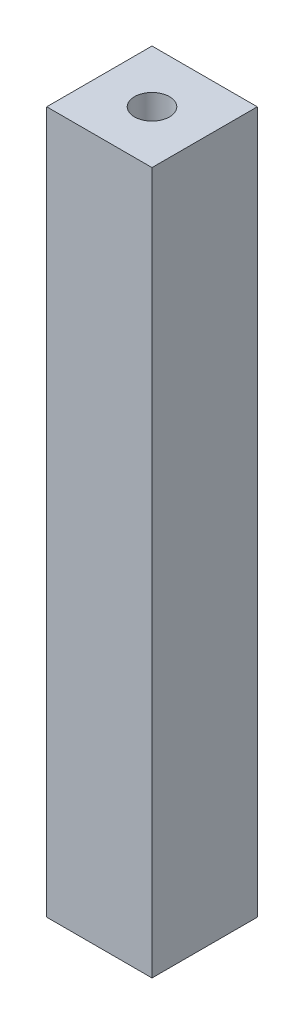
SolidWorks part; units mm, degrees
ref_plane "Front Plane" through (0, 0, 0) normal (0, 0, 1) x (1, 0, 0)
ref_plane "Top Plane" through (0, 0, 0) normal (0, 1, 0) x (1, 0, 0)
ref_plane "Right Plane" through (0, 0, 0) normal (1, 0, 0) x (0, 0, -1)
sketch "Sketch1" plane through (0, 0, 0) normal (0, 1, 0) x (1, 0, 0)
  line L1 (7.5, -7.5) -> (-7.5, -7.5)
  line L2 (7.5, -7.5) -> (7.5, 7.5)
  line L3 (7.5, 7.5) -> (-7.5, 7.5)
  line L4 (-7.5, -7.5) -> (-7.5, 7.5)
  line L5 (7.5, -7.5) -> (-7.5, 7.5) construction
  line L6 (7.5, 7.5) -> (-7.5, -7.5) construction
  circle A0 centre (0, 0) radius 2.5
  point P0 (0, 0)
  dimension "D1" = 15
  dimension "D2" = 15
extrude "Boss-Extrude1" add sketch "Sketch1" along normal blind 100
